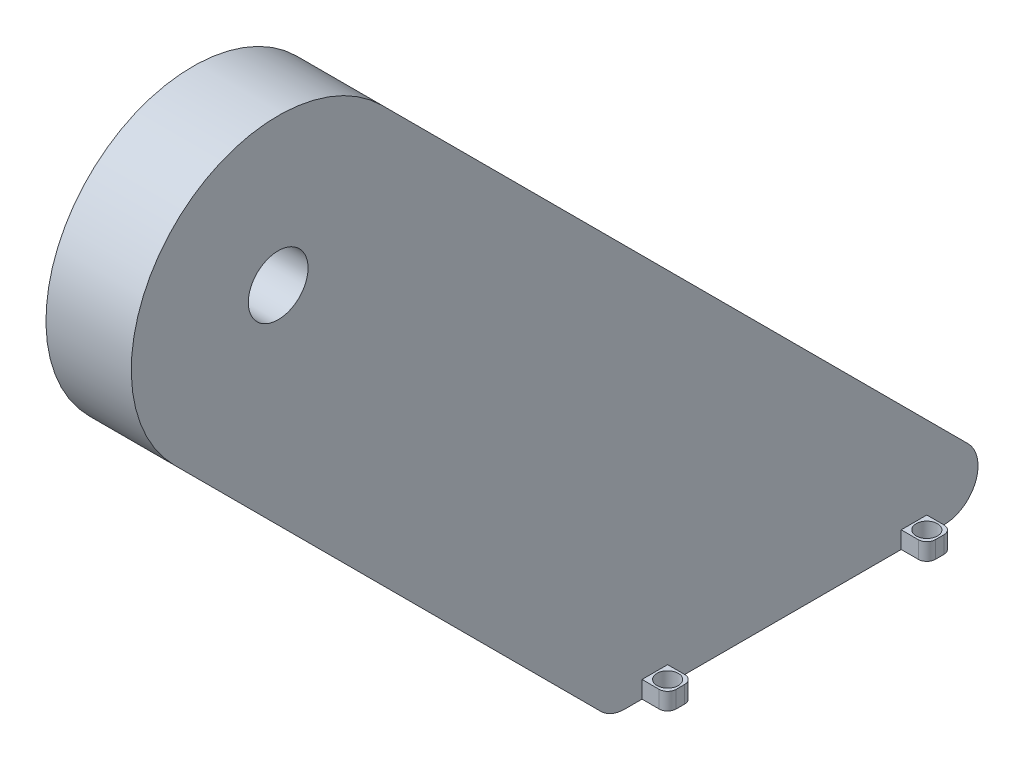
SolidWorks part; units mm, degrees
ref_plane "Front Plane" through (0, 0, 0) normal (0, 0, 1) x (1, 0, 0)
ref_plane "Top Plane" through (0, 0, 0) normal (0, 1, 0) x (1, 0, 0)
ref_plane "Right Plane" through (0, 0, 0) normal (1, 0, 0) x (0, 0, -1)
sketch "Sketch1" plane through (0, 0, 0) normal (1, 0, 0) x (0, 0, -1)
  line L0 (0, 0) -> (-13.3431, 0)
  line L1 (0, 0) -> (24.0294, 0)
  line L2 (-16.1716, 1.1716) -> (-66.1543, 51.1543)
  line L3 (26.8579, 6.8284) -> (-41.8112, 75.4975)
  arc A0 (-41.8112, 75.4975) -> (-66.1543, 51.1543) centre (-53.9828, 63.3259) ccw
  arc A1 (24.0294, 0) -> (26.8579, 6.8284) centre (24.0294, 4) ccw
  arc A2 (-13.3431, 0) -> (-16.1716, 1.1716) centre (-13.3431, 4) cw
  circle A3 centre (-53.9828, 63.3259) radius 3.5
  dimension "D1" = 37.3726
  dimension "D2" = 97.1127
  dimension "D3" = 70.6863
  dimension "D4" = 17.2132
extrude "Boss-Extrude2" add sketch "Sketch1" along normal blind 10
sketch "Sketch2" plane through (0, 0, 0) normal (0, -1, 0) x (1, 0, 0)
  line L0 (10, 13.3431) -> (10, -24.0294) construction
  line L1 (10, 11.3431) -> (13, 11.3431)
  line L2 (10, 11.3431) -> (10, 8.3431)
  line L3 (10, 8.3431) -> (13, 8.3431)
  line L4 (13, 11.3431) -> (13, 8.3431)
  line L5 (10, 13.3431) -> (0, 13.3431) construction
  line L6 (10, -19.0294) -> (13, -19.0294)
  line L7 (10, -19.0294) -> (10, -22.0294)
  line L8 (10, -22.0294) -> (13, -22.0294)
  line L9 (13, -19.0294) -> (13, -22.0294)
  line L10 (10, -24.0294) -> (0, -24.0294) construction
  circle A0 centre (11.5, 9.8431) radius 1.25
  circle A1 centre (11.5, -20.5294) radius 1.25
  dimension "D6" = 1.5
  dimension "D1" = 2
  dimension "D2" = 2
  dimension "D3" = 5
  dimension "D4" = 3
  dimension "D5" = 3
  dimension "D7" = 1.5
  dimension "D8" = 1.5
  dimension "D9" = 1.5
  dimension "D10" = 3
extrude "Boss-Extrude3" add sketch "Sketch2" against normal blind 2
fillet "Fillet2" radius 1 1 edges at (13, 1, 11.3431)
fillet "Fillet6" radius 1 1 edges at (13, 1, 8.3431)
fillet "Fillet7" radius 1 2 edges at (13, 1, -19.0294) (13, 1, -22.0294)
